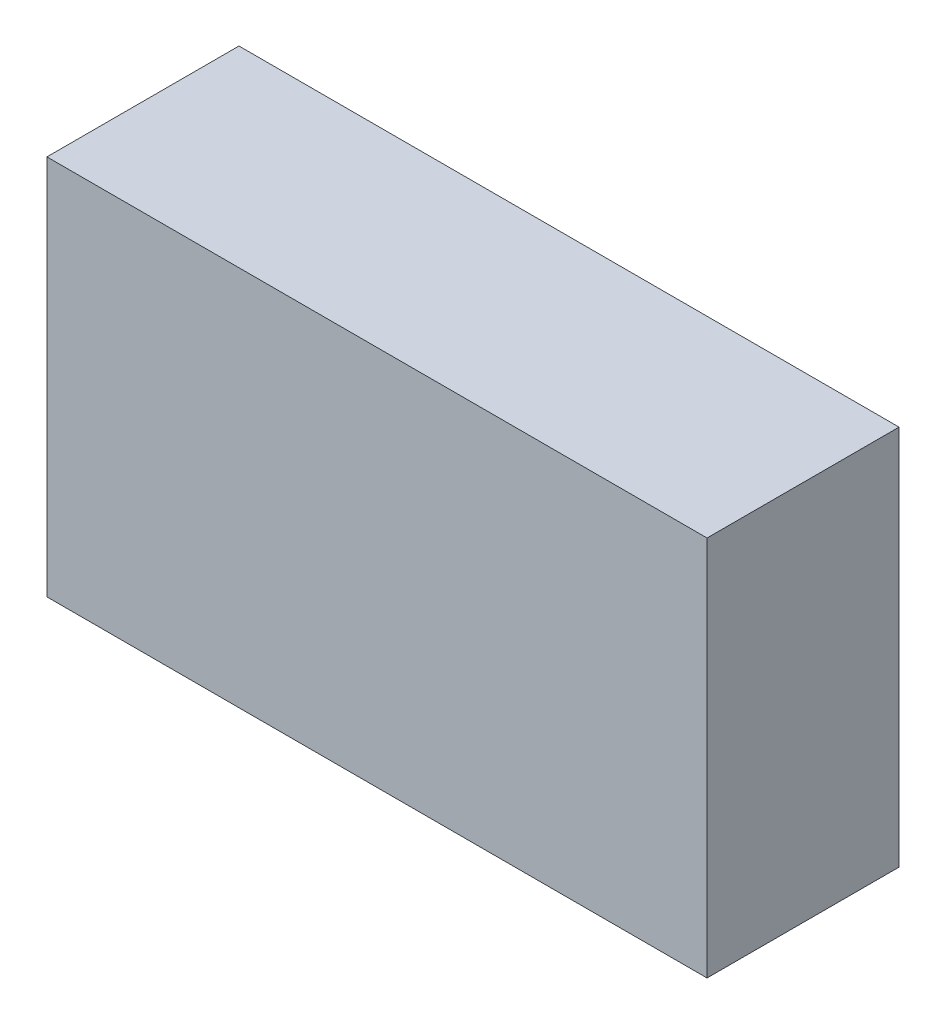
SolidWorks part; units mm, degrees
ref_plane "Alzado" through (0, 0, 0) normal (0, 0, 1) x (1, 0, 0)
ref_plane "Planta" through (0, 0, 0) normal (0, 1, 0) x (1, 0, 0)
ref_plane "Vista lateral" through (0, 0, 0) normal (1, 0, 0) x (0, 0, -1)
sketch "Croquis1" plane through (0, 0, 0) normal (0, 0, 1) x (1, 0, 0)
  line L1 (-55, 31.75) -> (55, 31.75)
  line L2 (-55, 31.75) -> (-55, -31.75)
  line L3 (-55, -31.75) -> (55, -31.75)
  line L4 (55, 31.75) -> (55, -31.75)
  line L5 (-55, 31.75) -> (55, -31.75) construction
  line L6 (-55, -31.75) -> (55, 31.75) construction
  point P0 (0, 0)
  dimension "D1" = 110
  dimension "D2" = 63.5
extrude "Saliente-Extruir1" add sketch "Croquis1" along normal blind 32
sketch "Croquis2" plane through (0, 0, 32) normal (0, 0, 1) x (1, 0, 0)
  line L1 (52.5, -30) -> (-52.5, -30)
  line L2 (52.5, -30) -> (52.5, 30)
  line L3 (52.5, 30) -> (-52.5, 30)
  line L4 (-52.5, -30) -> (-52.5, 30)
  line L5 (52.5, -30) -> (-52.5, 30) construction
  line L6 (52.5, 30) -> (-52.5, -30) construction
  point P0 (0, 0)
  dimension "D1" = 60
  dimension "D2" = 105
